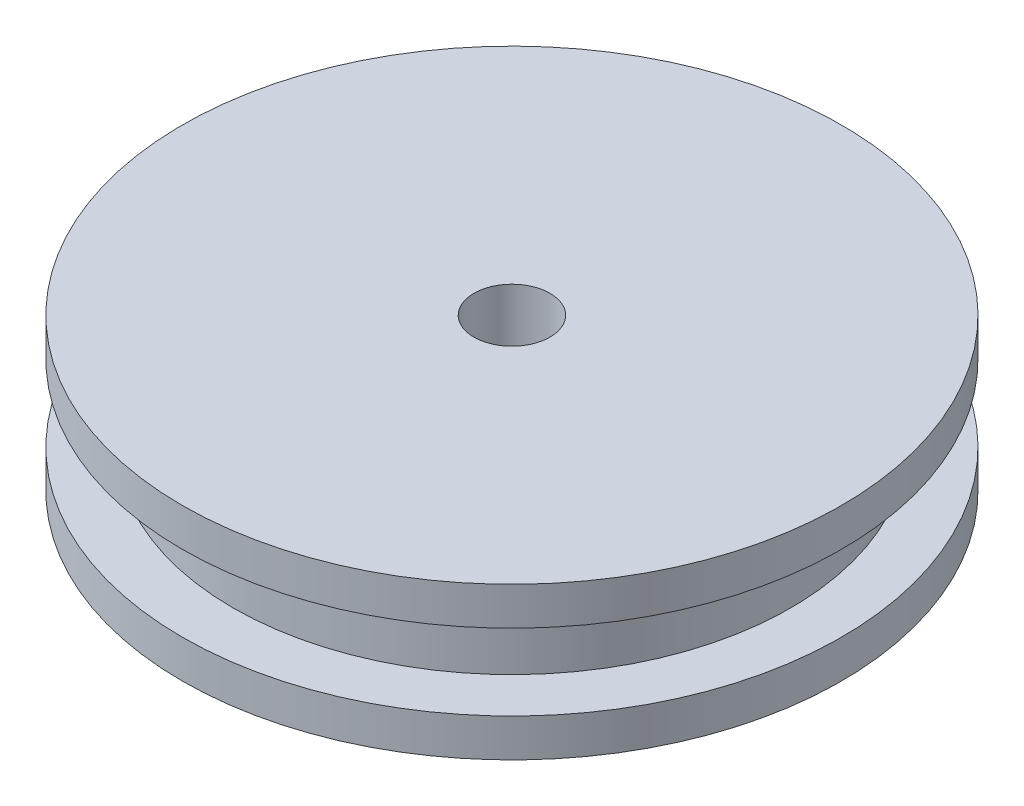
SolidWorks part; units mm, degrees
material "Custom Plastic"
ref_plane "Front Plane" through (0, 0, 0) normal (0, 0, 1) x (1, 0, 0)
ref_plane "Top Plane" through (0, 0, 0) normal (0, 1, 0) x (1, 0, 0)
ref_plane "Right Plane" through (0, 0, 0) normal (1, 0, 0) x (0, 0, -1)
other "Configuration Table"
sketch "Sketch2" plane through (0, 0, 0) normal (0, 0, 1) x (1, 0, 0)
  line L0 (0, 36.5649) -> (0, -39.5397) construction
  line L1 (0, 16.6116) -> (-82.55, 16.6116)
  line L2 (-82.55, 16.6116) -> (-82.55, 7.0866)
  line L3 (-82.55, 7.0866) -> (-69.85, 7.0866)
  line L4 (-69.85, 7.0866) -> (-69.85, -11.9634)
  line L5 (-69.85, -11.9634) -> (-82.55, -11.9634)
  line L6 (-82.55, -11.9634) -> (-82.55, -21.4884)
  line L7 (-82.55, -21.4884) -> (0, -21.4884)
  line L8 (0, -21.4884) -> (0, 16.6116)
  dimension "D1" = 165.1
  dimension "D2" = 38.1
  dimension "D3" = 19.05
  dimension "D4" = 9.525
  dimension "D5" = 12.7
revolve "Revolve1" add sketch "Sketch2" angle 360 about L0
sketch "Sketch3" plane through (0, 16.6116, 0) normal (0, 1, 0) x (1, 0, 0)
  line L0 (0, 0) -> (0, -94.4367) construction
sketch "Sketch4" plane through (0, 16.6116, 0) normal (0, 1, 0) x (1, 0, 0)
  circle A0 centre (0, 0) radius 9.525
  dimension "D1" = 19.05
extrude "Cut-Extrude1" cut sketch "Sketch4" against normal through all
sketch "Sketch5" [suppressed] plane through (0, 0, 0) normal (0, 1, 0) x (1, 0, 0)
  circle A0 centre (0, 0) radius 38.1
  circle A1 centre (0, 0) radius 9.525
  dimension "D1" = 76.2
  dimension "D2" = 19.05
extrude "Boss-Extrude1" [suppressed] add sketch "Sketch5" along normal blind 12.7
